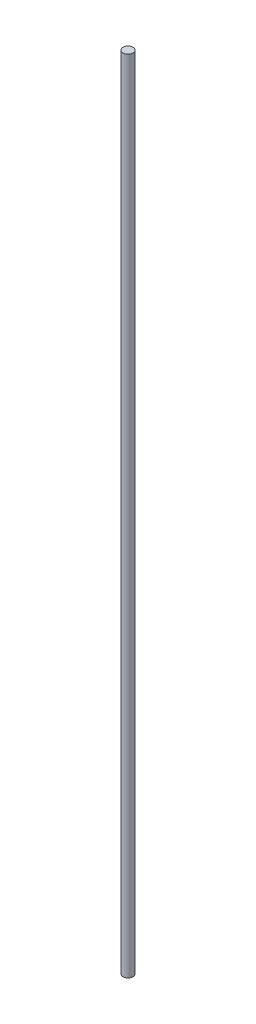
SolidWorks part; units mm, degrees
ref_plane "Front Plane" through (0, 0, 0) normal (0, 0, 1) x (1, 0, 0)
ref_plane "Top Plane" through (0, 0, 0) normal (0, 1, 0) x (1, 0, 0)
ref_plane "Right Plane" through (0, 0, 0) normal (1, 0, 0) x (0, 0, -1)
sketch "Sketch1" plane through (0, 0, 0) normal (0, 1, 0) x (1, 0, 0)
  circle A0 centre (0, 0) radius 1.575
  dimension "D1" = 3.15
extrude "Boss-Extrude1" add sketch "Sketch1" along normal blind 250
